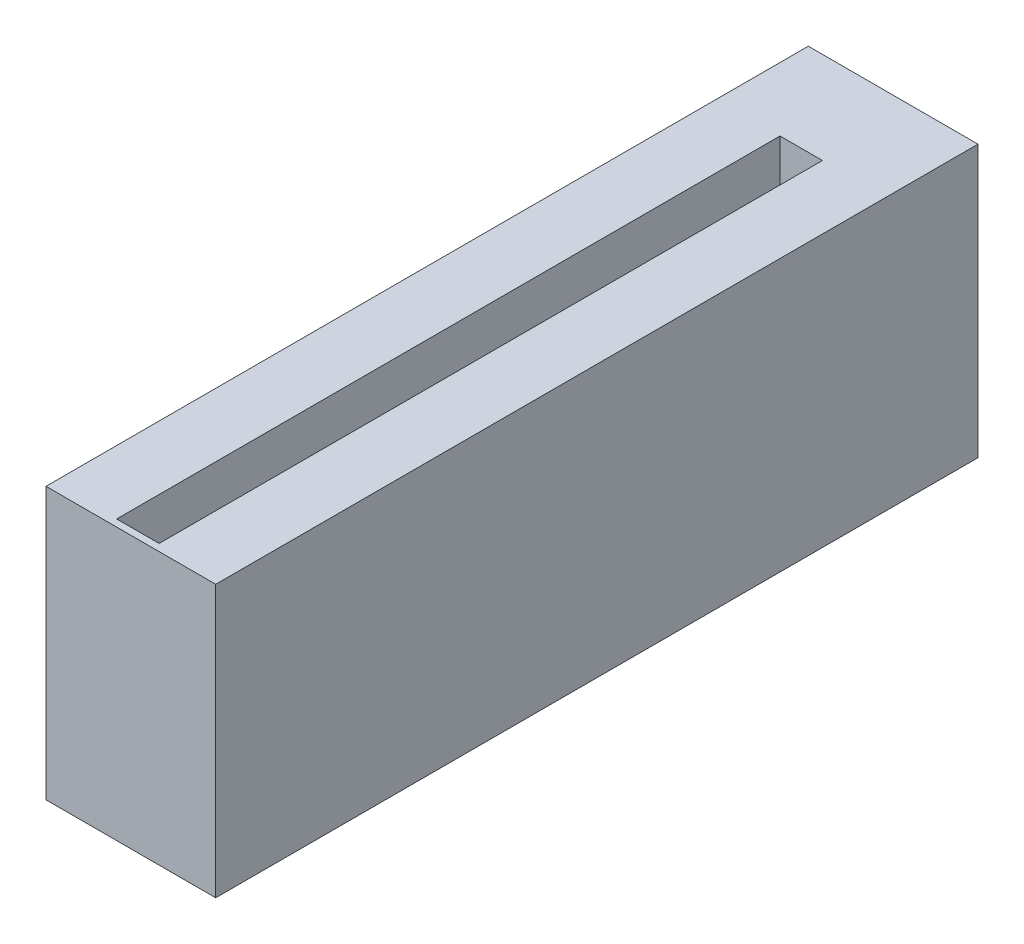
SolidWorks part; units mm, degrees
ref_plane "Front Plane" through (0, 0, 0) normal (0, 0, 1) x (1, 0, 0)
ref_plane "Top Plane" through (0, 0, 0) normal (0, 1, 0) x (1, 0, 0)
ref_plane "Right Plane" through (0, 0, 0) normal (1, 0, 0) x (0, 0, -1)
sketch "Sketch2" plane through (0, 0, 0) normal (0, 1, 0) x (1, 0, 0)
  line L0 (0, 0) -> (0, 26.95)
  line L1 (0, 26.95) -> (6, 26.95)
  line L2 (6, 26.95) -> (6, 0)
  line L3 (6, 0) -> (0, 0)
  dimension "D1" = 26.95
  dimension "D2" = 6
extrude "Boss-Extrude1" add sketch "Sketch2" along normal blind 9.6 contours L1 L2 L3 L0
sketch "Sketch3" plane through (0, 9.6, 0) normal (0, 1, 0) x (1, 0, 0)
  line L0 (3, 26.95) -> (3, 0) construction
  line L1 (0, 26.95) -> (6, 26.95) construction
  line L2 (6, 0) -> (0, 0) construction
  line L3 (3, 26.95) -> (2.25, 26.95)
  line L4 (2.25, 26.95) -> (2.25, 0)
  line L5 (2.25, 0) -> (3.75, 0)
  line L6 (3.75, 0) -> (3.75, 26.95)
  line L7 (3.75, 26.95) -> (3, 26.95)
  dimension "D1" = 0.75
  dimension "D2" = 0.75
extrude "Cut-Extrude2" cut sketch "Sketch3" against normal up to surface (9.6 mm away) up to face at (3, 0, -13.475)
sketch "Sketch5" plane through (0, 0, 0) normal (0, -1, 0) x (1, 0, 0)
  line L0 (2.25, -26.95) -> (3.75, -26.95) construction
  line L1 (2.25, 0) -> (3.75, 0) construction
  line L2 (3, -26.95) -> (3, 0) construction
sketch "Sketch7" plane through (0, 9.6, 0) normal (0, 1, 0) x (1, 0, 0)
  line L0 (3.75, 0) -> (2.25, 0)
  line L1 (2.25, 0) -> (2.25, 0.25)
  line L2 (2.25, 26.95) -> (2.25, 0) construction
  line L3 (2.25, 0.25) -> (3.75, 0.25)
  line L4 (3.75, 0) -> (3.75, 26.95) construction
  line L5 (3.75, 0.25) -> (3.75, 0)
  dimension "D1" = 0.25
extrude "Boss-Extrude2" add sketch "Sketch7" against normal up to surface (9.6 mm away) up to face at (1.125, 0, -13.475)
sketch "Sketch8" plane through (0, 9.6, 0) normal (0, 1, 0) x (1, 0, 0)
  line L0 (2.25, 26.95) -> (3.75, 26.95)
  line L1 (3.75, 26.95) -> (3.75, 23.7)
  line L2 (3.75, 0.25) -> (3.75, 26.95) construction
  line L3 (3.75, 23.7) -> (2.25, 23.7)
  line L4 (2.25, 26.95) -> (2.25, 0.25) construction
  line L5 (2.25, 23.7) -> (2.25, 26.95)
  dimension "D1" = 3.25
extrude "Boss-Extrude3" add sketch "Sketch8" against normal up to surface (9.6 mm away) up to face at (3, 0, -13.5375)
